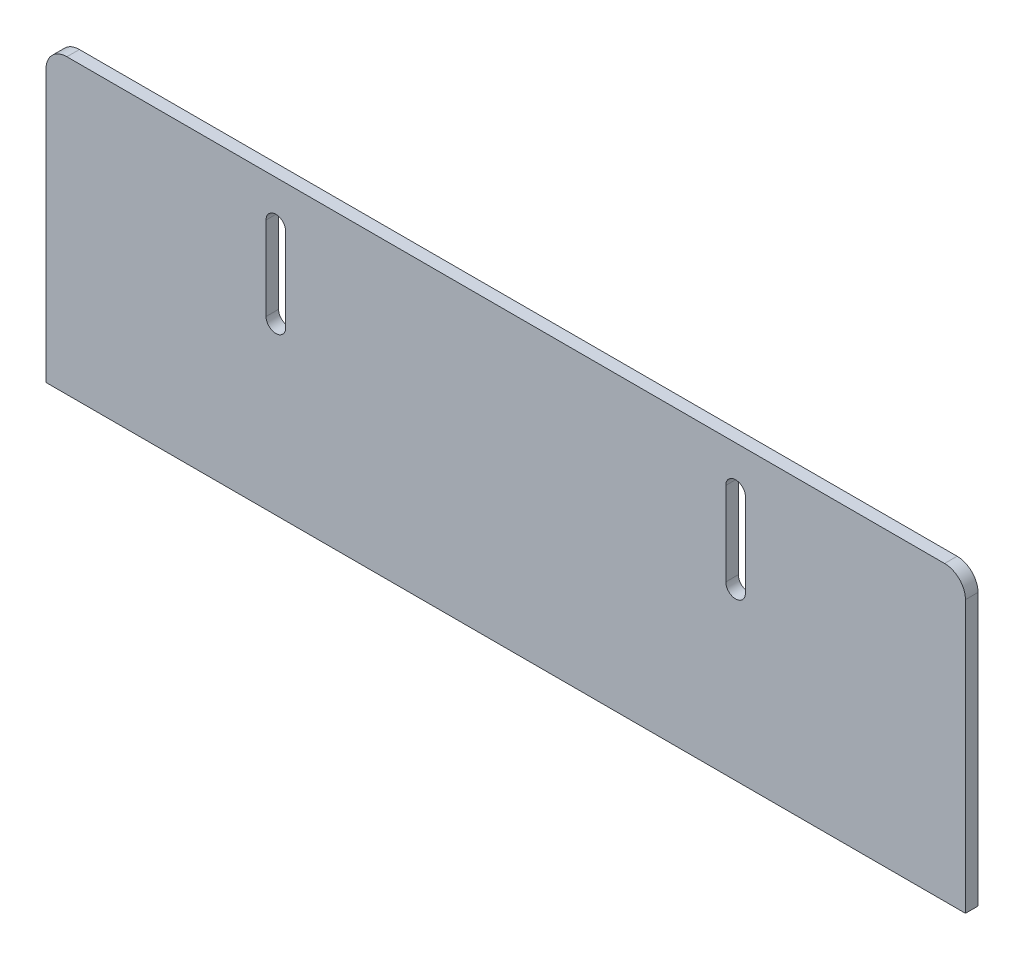
SolidWorks part; units mm, degrees
ref_plane "前视基准面" through (0, 0, 0) normal (0, 0, 1) x (1, 0, 0)
ref_plane "上视基准面" through (0, 0, 0) normal (0, 1, 0) x (1, 0, 0)
ref_plane "右视基准面" through (0, 0, 0) normal (1, 0, 0) x (0, 0, -1)
sketch "草图1" plane through (0, 0, 0) normal (0, 0, 1) x (1, 0, 0)
  line L0 (110, 70) -> (110, 0) construction
  line L1 (0, 0) -> (220, 0)
  line L2 (0, 0) -> (0, 65)
  line L3 (5, 70) -> (215, 70)
  line L4 (220, 0) -> (220, 65)
  line L5 (52.649, 60) -> (52.649, 40)
  line L6 (57.351, 60) -> (57.351, 40)
  line L7 (162.649, 60) -> (162.649, 40)
  line L8 (167.351, 60) -> (167.351, 40)
  arc A0 (57.351, 60) -> (52.649, 60) centre (55, 60) ccw
  arc A1 (52.649, 40) -> (57.351, 40) centre (55, 40) ccw
  arc A2 (167.351, 40) -> (162.649, 40) centre (165, 40) cw
  arc A3 (162.649, 60) -> (167.351, 60) centre (165, 60) cw
  arc A4 (220, 65) -> (215, 70) centre (215, 65) ccw
  arc A5 (0, 65) -> (5, 70) centre (5, 65) cw
  dimension "D1" = 55
  dimension "D3" = 5
  dimension "D2" = 20
  dimension "D4" = 220
  dimension "D5" = 55
  dimension "D6" = 70
  dimension "D7" = 10
  dimension "D8" = 10
extrude "凸台-拉伸1" add sketch "草图1" along normal blind 3
